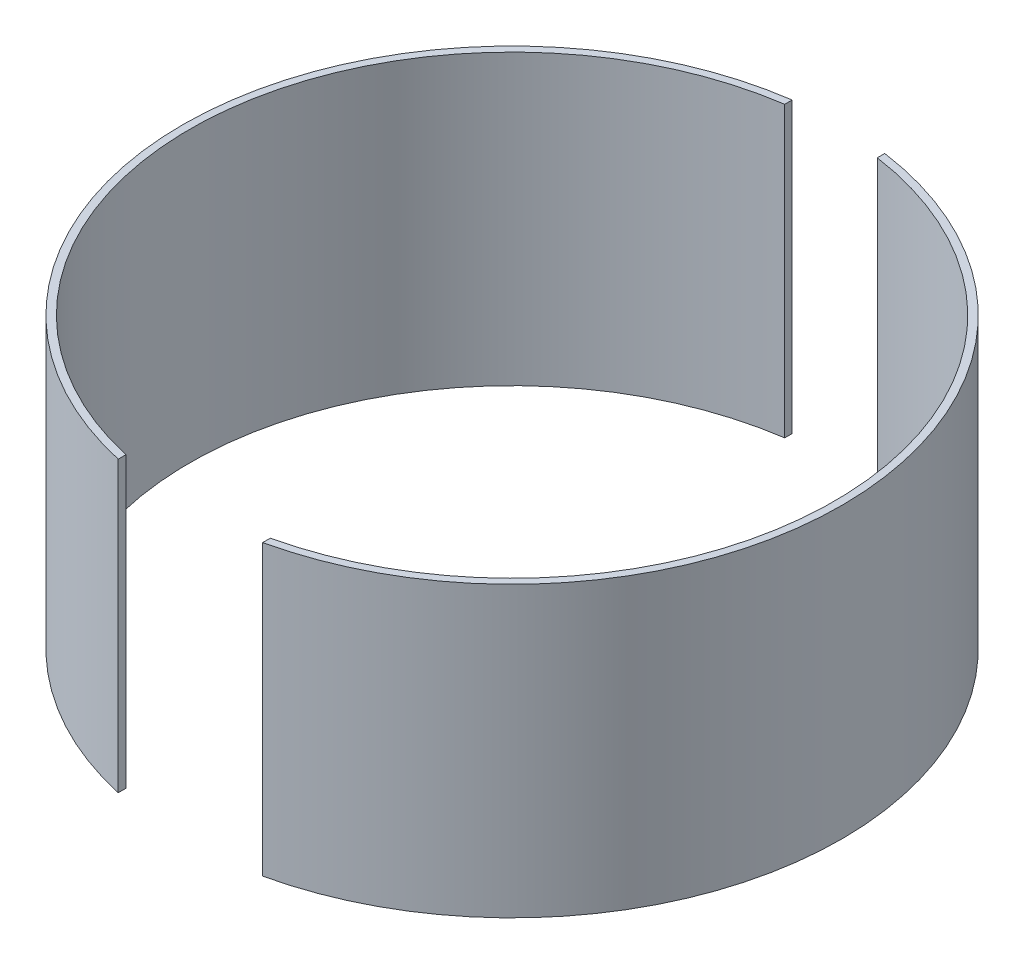
SolidWorks part; units mm, degrees
ref_plane "Front Plane" through (0, 0, 0) normal (0, 0, 1) x (1, 0, 0)
ref_plane "Top Plane" through (0, 0, 0) normal (0, 1, 0) x (1, 0, 0)
ref_plane "Right Plane" through (0, 0, 0) normal (1, 0, 0) x (0, 0, -1)
sketch "Sketch1" plane through (0, 0, 0) normal (0, 1, 0) x (1, 0, 0)
  circle A0 centre (0, 0) radius 87
  circle A1 centre (0, 0) radius 89
  dimension "D1" = 174
  dimension "D2" = 178
extrude "Boss-Extrude1" add sketch "Sketch1" along normal blind 78
sketch "Sketch2" plane through (0, 0, 0) normal (0, 0, 1) x (1, 0, 0)
  line L0 (-89, 0) -> (-89, 78)
  line L1 (89, 78) -> (89, 0)
  line L2 (89, 78) -> (89, 0)
  line L3 (-89, 0) -> (-89, 78)
  line L4 (-89, 0) -> (89, 0) construction
  line L5 (-12.5, 0) -> (12.5, 0)
  line L6 (-12.5, 0) -> (-12.5, 78)
  line L7 (-12.5, 78) -> (12.5, 78)
  line L8 (12.5, 0) -> (12.5, 78)
  line L9 (-12.5, 0) -> (12.5, 78) construction
  line L10 (-12.5, 78) -> (12.5, 0) construction
  line L11 (87, 78) -> (-87, 78) construction
  point P8 (0, 39)
  dimension "D1" = 12.5
extrude "Cut-Extrude1" cut sketch "Sketch2" against normal blind 100 contours L5 L8 L7 L6
sketch "Sketch3" plane through (0, 0, 0) normal (0, 0, 1) x (1, 0, 0)
  line L0 (-89, 0) -> (89, 0) construction
  line L1 (-19.5, 0) -> (19.5, 0)
  line L2 (-19.5, 0) -> (-19.5, 78)
  line L3 (-19.5, 78) -> (19.5, 78)
  line L4 (19.5, 0) -> (19.5, 78)
  line L5 (-19.5, 0) -> (19.5, 78) construction
  line L6 (-19.5, 78) -> (19.5, 0) construction
  line L7 (87, 78) -> (-87, 78) construction
  point P4 (0, 39)
  dimension "D1" = 39
extrude "Cut-Extrude2" cut sketch "Sketch3" along normal blind 208
